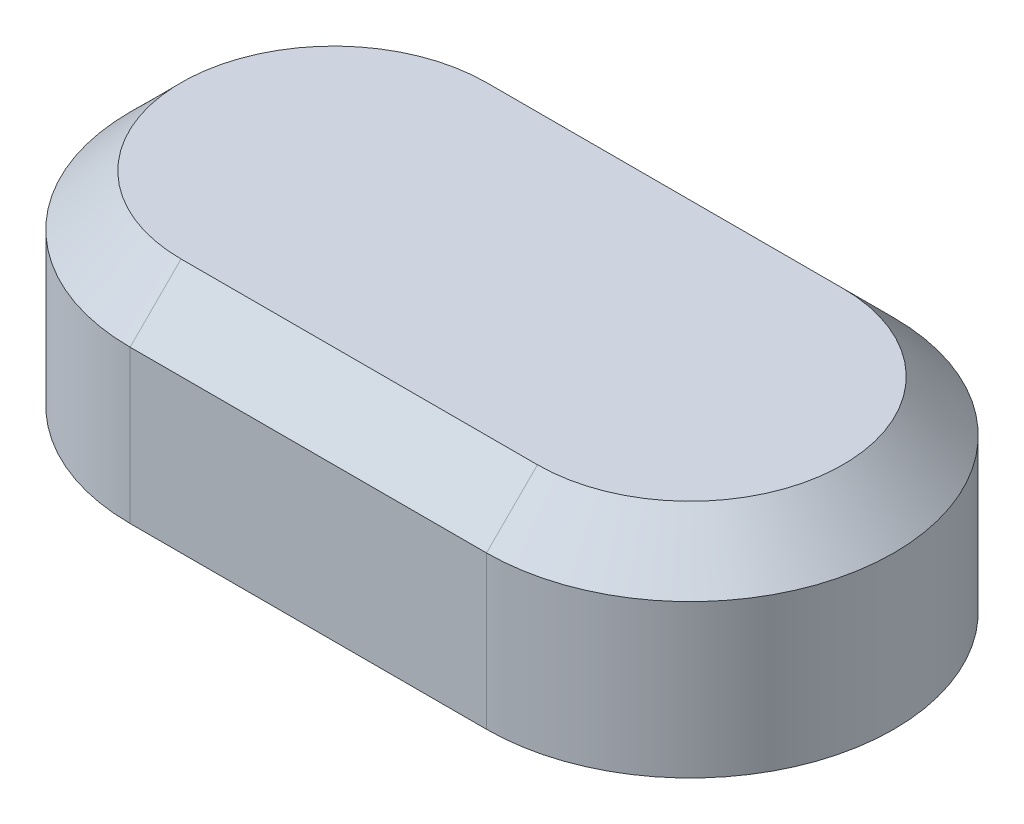
SolidWorks part; units mm, degrees
ref_plane "Plan de face" through (0, 0, 0) normal (0, 0, 1) x (1, 0, 0)
ref_plane "Plan de dessus" through (0, 0, 0) normal (0, 1, 0) x (1, 0, 0)
ref_plane "Plan de droite" through (0, 0, 0) normal (1, 0, 0) x (0, 0, -1)
sketch "Esquisse1" plane through (0, 0, 0) normal (0, 1, 0) x (1, 0, 0)
  line L0 (-3.5, 0) -> (3.5, 0) construction
  line L1 (-3.5, 4) -> (3.5, 4)
  line L2 (-3.5, -4) -> (3.5, -4)
  arc A0 (-3.5, 4) -> (-3.5, -4) centre (-3.5, 0) ccw
  arc A1 (3.5, -4) -> (3.5, 4) centre (3.5, 0) ccw
  point P2 (0, 0)
  point P7 (-7.5, 0)
  point P8 (7.5, 0)
  dimension "D1" = 8
  dimension "D2" = 15
extrude "Boss.-Extru.1" add sketch "Esquisse1" along normal blind 4
chamfer "Chanfrein1" distance 1 angle 45 4 edges at (-7.5, 4, 0) (0, 4, -4) (7.5, 4, 0) (0, 4, 4)
